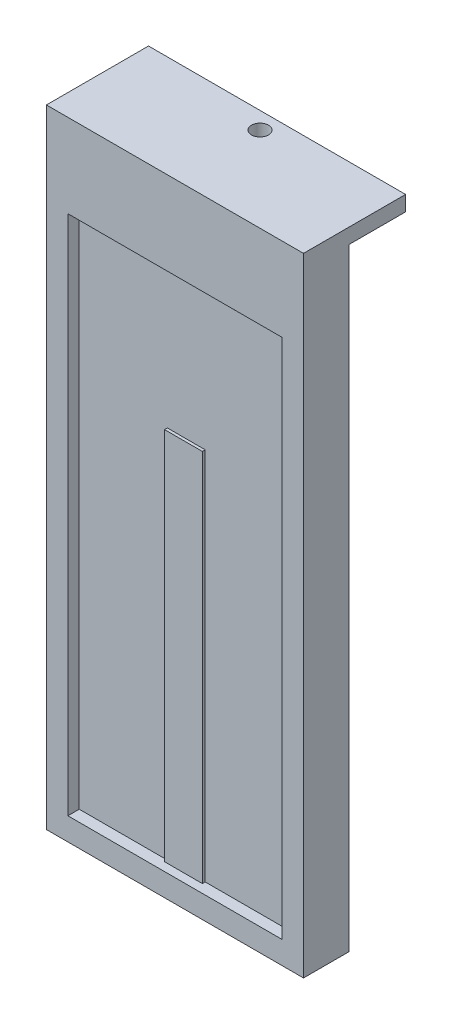
SolidWorks part; units mm, degrees
ref_plane "Front Plane" through (0, 0, 0) normal (0, 0, 1) x (1, 0, 0)
ref_plane "Top Plane" through (0, 0, 0) normal (0, 1, 0) x (1, 0, 0)
ref_plane "Right Plane" through (0, 0, 0) normal (1, 0, 0) x (0, 0, -1)
sketch "Sketch1" plane through (0, 0, 0) normal (0, 0, 1) x (1, 0, 0)
  line L1 (-34, -81) -> (34, -81)
  line L2 (-34, -81) -> (-34, 81)
  line L3 (-34, 81) -> (34, 81)
  line L4 (34, -81) -> (34, 81)
  line L5 (-34, -81) -> (34, 81) construction
  line L6 (-34, 81) -> (34, -81) construction
  point P0 (0, 0)
  dimension "D1" = 162
  dimension "D2" = 68
extrude "Boss-Extrude1" add sketch "Sketch1" along normal blind 12
sketch "Sketch2" plane through (0, 81, 0) normal (0, 1, 0) x (1, 0, 0)
  line L0 (34, 0) -> (-34, 0) construction
  line L1 (-34, -12) -> (34, -12)
  line L2 (-34, -12) -> (-34, 15)
  line L3 (-34, 15) -> (34, 15)
  line L4 (34, -12) -> (34, 15)
  dimension "D1" = 15
extrude "Boss-Extrude2" add sketch "Sketch2" along normal blind 4
sketch "Sketch4" plane through (0, 85, 0) normal (0, 1, 0) x (1, 0, 0)
  line L0 (0, -12) -> (0, 15) construction
  line L1 (-34, -12) -> (34, -12) construction
  line L2 (34, 15) -> (-34, 15) construction
  circle A0 centre (0, 10.5) radius 2.25
  dimension "D1" = 4.5
  dimension "D2" = 4.5
extrude "Cut-Extrude1" cut sketch "Sketch4" against normal through all
sketch "Sketch5" plane through (0, 0, 12) normal (0, 0, 1) x (1, 0, 0)
  line L0 (0, 85) -> (0, -81) construction
  line L1 (-34, 85) -> (34, 85) construction
  line L2 (-34, -81) -> (34, -81) construction
  line L4 (-28.321, -75) -> (28.321, -75)
  line L5 (-28.321, -75) -> (-28.321, 62.922)
  line L6 (-28.321, 62.922) -> (28.321, 62.922)
  line L7 (28.321, -75) -> (28.321, 62.922)
  line L8 (-28.321, -75) -> (28.321, 62.922) construction
  line L9 (-28.321, 62.922) -> (28.321, -75) construction
  point P6 (0, -6.039)
  point P11 (0, -2.6569)
  dimension "D1" = 137.922
  dimension "D2" = 56.642
  dimension "D3" = 6
extrude "Cut-Extrude2" cut sketch "Sketch5" against normal blind 3
sketch "Sketch6" plane through (0, 0, 9) normal (0, 0, 1) x (1, 0, 0)
  line L0 (0, -75) -> (0, 62.922) construction
  line L1 (-28.321, -75) -> (28.321, -75) construction
  line L2 (28.321, 62.922) -> (-28.321, 62.922) construction
  line L4 (-5, 24) -> (5, 24)
  line L5 (-5, 24) -> (-5, -75)
  line L6 (-5, -75) -> (5, -75)
  line L7 (5, 24) -> (5, -75)
  line L8 (-5, 24) -> (5, -75) construction
  line L9 (-5, -75) -> (5, 24) construction
  point P6 (0, -25.5)
  dimension "D1" = 10
  dimension "D2" = 99
extrude "Boss-Extrude3" add sketch "Sketch6" along normal blind 0.746
